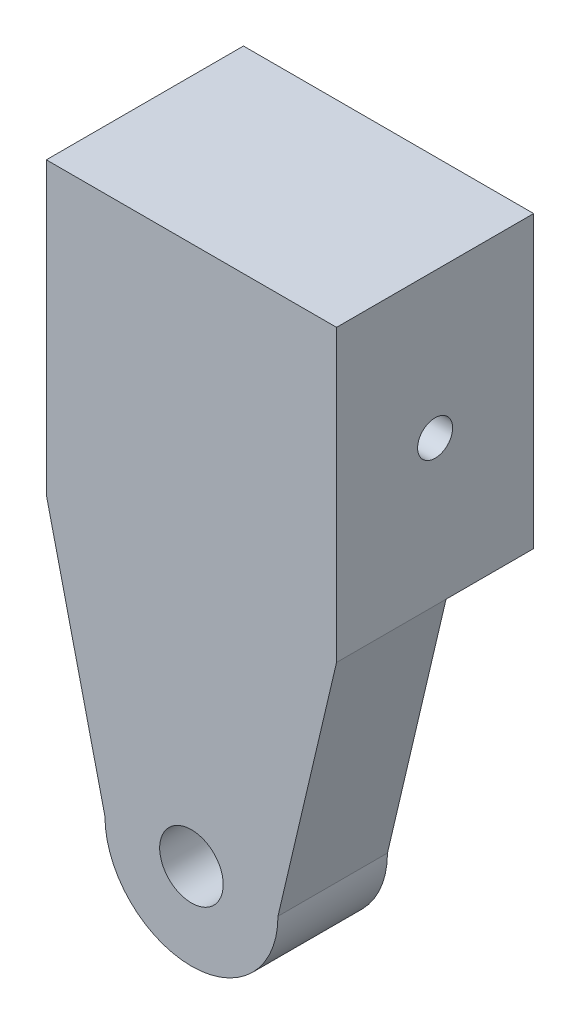
SolidWorks part; units mm, degrees
ref_plane "Alzado" through (0, 0, 0) normal (0, 0, 1) x (1, 0, 0)
ref_plane "Planta" through (0, 0, 0) normal (0, 1, 0) x (1, 0, 0)
ref_plane "Vista lateral" through (0, 0, 0) normal (1, 0, 0) x (0, 0, -1)
sketch "Croquis1" plane through (0, 0, 0) normal (0, 0, 1) x (1, 0, 0)
  line L0 (13.25, 13.25) -> (-13.25, 13.25)
  line L1 (10.25, -10.25) -> (-10.25, -10.25)
  line L2 (10.25, -10.25) -> (10.25, 10.25)
  line L3 (10.25, 10.25) -> (-10.25, 10.25)
  line L4 (-10.25, -10.25) -> (-10.25, 10.25)
  line L5 (10.25, -10.25) -> (-10.25, 10.25) construction
  line L6 (10.25, 10.25) -> (-10.25, -10.25) construction
  line L7 (-13.25, -13.25) -> (-13.25, 13.25)
  line L8 (13.25, -13.25) -> (-13.25, -13.25)
  line L9 (13.25, -13.25) -> (13.25, 13.25)
  point P0 (0, 0)
  dimension "D1" = 20.5
  dimension "D2" = 20.5
  dimension "D3" = 3
extrude "Saliente-Extruir1" add sketch "Croquis1" along normal mid plane 18
sketch "Croquis2" plane through (0, 0, 0) normal (0, 0, 1) x (1, 0, 0)
  line L0 (-7.9, -36) -> (-13.25, -13.25)
  line L1 (-13.25, -13.25) -> (13.25, -13.25) construction
  line L2 (-13.25, -13.25) -> (13.25, -13.25)
  line L3 (13.25, -13.25) -> (7.9, -36)
  line L4 (0, -35) -> (0, 55.3993) construction
  circle A0 centre (0, -36) radius 2.9
  arc A1 (-7.9, -36) -> (7.9, -36) centre (0, -36) ccw
  circle A2 centre (0, -36) radius 7.9 construction
  point P0 (-1.9921, -35)
  point P2 (-13.25, -13.25)
  point P4 (-7.9, -35)
  point P13 (-7.9, -35)
  point P14 (0, -35)
  point P15 (7.9, -35)
  point P16 (0, 0)
  point P17 (0, 0)
  point P20 (-0.0862, -35.9985)
  dimension "D1" = 5.8
  dimension "D3" = 36
  dimension "D4" = 26.5
  dimension "D2" = 5
extrude "Saliente-Extruir2" add sketch "Croquis2" along normal up to surface (9 mm away) and the other way blind 1 up to face at (0, 0, 9)
sketch "Croquis5" plane through (0, 0, 9) normal (0, 0, 1) x (1, 0, 0)
  line L0 (10.25, 10.25) -> (-10.25, 10.25) construction
  line L1 (10.25, 10.25) -> (-10.25, 10.25)
  line L2 (-10.25, 10.25) -> (-10.25, -10.25) construction
  line L3 (-10.25, 10.25) -> (-10.25, -10.25)
  line L4 (10.25, -10.25) -> (10.25, 10.25) construction
  line L5 (10.25, -10.25) -> (10.25, 10.25)
  line L6 (-10.25, -10.25) -> (10.25, -10.25) construction
  line L7 (-10.25, -10.25) -> (10.25, -10.25)
extrude "Saliente-Extruir3" add sketch "Croquis5" against normal blind 1
sketch "Croquis3" plane through (0, 0, 0) normal (1, 0, 0) x (0, 0, -1)
  line L0 (1, -28.25) -> (7.5, -13.25)
  line L1 (1, -36) -> (1, -13.25) construction
  line L3 (1, -13.25) -> (9, -13.25) construction
  dimension "D1" = 6.5
  dimension "D2" = 15
rib "Nervio6" sketch "Croquis3" sketch "Croquis3" thickness 10 extrusion direction parallel to sketch draft on no parameters "D1"=10
sketch "Croquis4" plane through (0, 0, 0) normal (1, 0, 0) x (0, 0, -1)
  circle A0 centre (0, 0) radius 1.6
  dimension "D1" = 3.2
extrude "Cortar-Extruir2" cut sketch "Croquis4" against normal mid plane 50 contours A0
